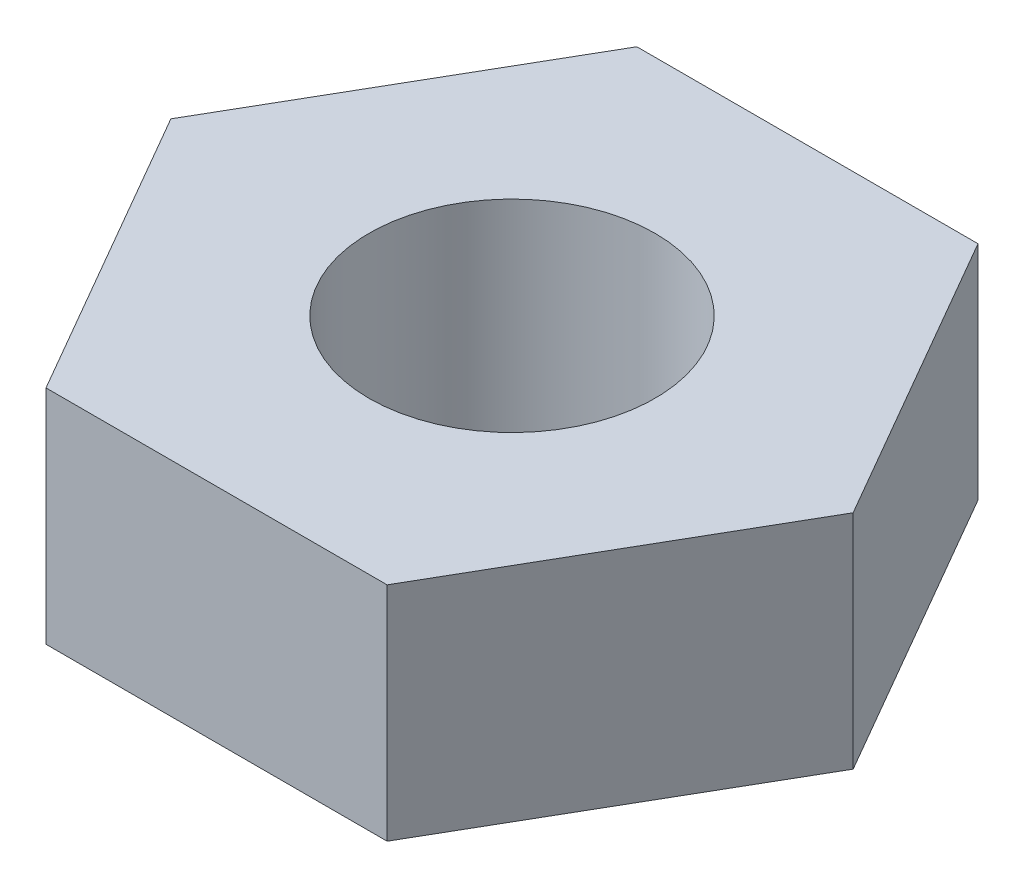
SolidWorks part; units mm, degrees
ref_plane "Front Plane" through (0, 0, 0) normal (0, 0, 1) x (1, 0, 0)
ref_plane "Top Plane" through (0, 0, 0) normal (0, 1, 0) x (1, 0, 0)
ref_plane "Right Plane" through (0, 0, 0) normal (1, 0, 0) x (0, 0, -1)
sketch "Sketch1" plane through (0, 0, 0) normal (0, 1, 0) x (1, 0, 0)
  line L1 (1.8129, 0) -> (0.9064, 1.57)
  line L2 (0.9064, 1.57) -> (-0.9064, 1.57)
  line L3 (-0.9064, 1.57) -> (-1.8129, 0)
  line L4 (-1.8129, 0) -> (-0.9064, -1.57)
  line L5 (-0.9064, -1.57) -> (0.9064, -1.57)
  line L6 (0.9064, -1.57) -> (1.8129, 0)
  circle A0 centre (0, 0) radius 1.57 construction
  dimension "D1" = 3.14
extrude "Boss-Extrude1" add sketch "Sketch1" along normal blind 1.18
sketch "Sketch2" plane through (0, 1.18, 0) normal (0, 1, 0) x (1, 0, 0)
  circle A0 centre (0, 0) radius 0.76
  dimension "D1" = 1.52
extrude "Cut-Extrude1" cut sketch "Sketch2" against normal through all
